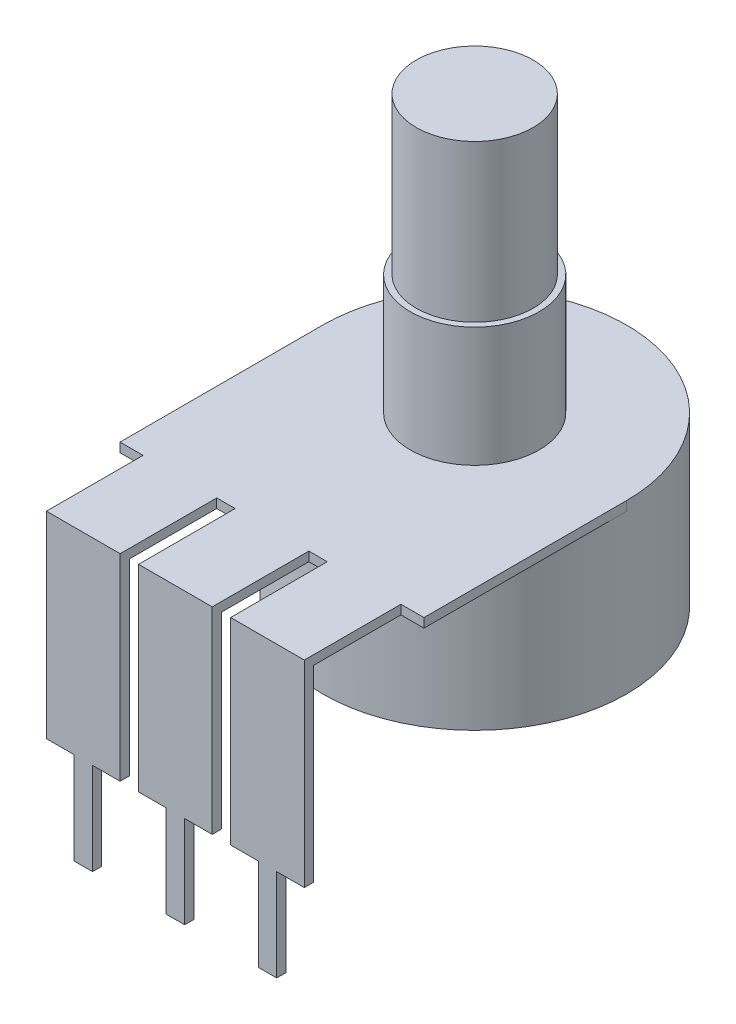
SolidWorks part; units mm, degrees
ref_plane "Front Plane" through (0, 0, 0) normal (0, 0, 1) x (1, 0, 0)
ref_plane "Top Plane" through (0, 0, 0) normal (0, 1, 0) x (1, 0, 0)
ref_plane "Right Plane" through (0, 0, 0) normal (1, 0, 0) x (0, 0, -1)
sketch "Sketch1" plane through (0, 0, 0) normal (0, 1, 0) x (1, 0, 0)
  circle A0 centre (0, 0) radius 8.25
  dimension "D1" = 16.5
extrude "Boss-Extrude1" add sketch "Sketch1" along normal blind 9.1
sketch "Sketch2" plane through (0, 9.1, 0) normal (0, 1, 0) x (1, 0, 0)
  circle A0 centre (0, 0) radius 3.5
  dimension "D1" = 7
extrude "Boss-Extrude2" add sketch "Sketch2" along normal blind 6.5
sketch "Sketch3" plane through (0, 15.6, 0) normal (0, 1, 0) x (1, 0, 0)
  circle A0 centre (0, 0) radius 3.175
  dimension "D1" = 6.35
extrude "Boss-Extrude3" add sketch "Sketch3" along normal blind 8.5
sketch "Sketch4" plane through (0, 9.1, 0) normal (0, 1, 0) x (1, 0, 0)
  line L0 (-8.25, 0) -> (-8.25, -16.25)
  line L1 (8.25, 0) -> (8.25, -16.25)
  line L2 (-8.25, -16.25) -> (8.25, -16.25)
  circle A0 centre (0, 0) radius 8.25 construction
  arc A1 (-8.25, 0) -> (8.25, 0) centre (0, 0) ccw
  dimension "D1" = 16.25
extrude "Boss-Extrude4" add sketch "Sketch4" against normal blind 0.5
sketch "Sketch5" plane through (0, 8.6, 0) normal (0, -1, 0) x (1, 0, 0)
  line L0 (0, 16.25) -> (0, 16) construction
  line L1 (-8.25, 16.25) -> (8.25, 16.25) construction
  line L2 (0, 16) -> (-5, 16) construction
  line L3 (-2, 16.25) -> (2, 16.25)
  line L4 (-2, 16.25) -> (-2, 15.75)
  line L5 (-2, 15.75) -> (2, 15.75)
  line L6 (2, 16.25) -> (2, 15.75)
  line L7 (-2, 16.25) -> (2, 15.75) construction
  line L8 (-2, 15.75) -> (2, 16.25) construction
  line L9 (0, 16) -> (5, 16) construction
  line L11 (-7, 16.25) -> (-3, 16.25)
  line L12 (-7, 16.25) -> (-7, 15.75)
  line L13 (-7, 15.75) -> (-3, 15.75)
  line L14 (-3, 16.25) -> (-3, 15.75)
  line L15 (-7, 16.25) -> (-3, 15.75) construction
  line L16 (-7, 15.75) -> (-3, 16.25) construction
  line L17 (3, 16.25) -> (7, 16.25)
  line L18 (3, 16.25) -> (3, 15.75)
  line L19 (3, 15.75) -> (7, 15.75)
  line L20 (7, 16.25) -> (7, 15.75)
  line L21 (3, 16.25) -> (7, 15.75) construction
  line L22 (3, 15.75) -> (7, 16.25) construction
  dimension "D1" = 5
  dimension "D2" = 5
  dimension "D3" = 0.5
  dimension "D4" = 4
extrude "Boss-Extrude5" add sketch "Sketch5" along normal offset from surface (10.2 mm away) 10.7 up to face at (0, 9.1, 3.5)
sketch "Sketch6" plane through (0, -1.6, 0) normal (0, -1, 0) x (1, 0, 0)
  line L0 (-5, 16.25) -> (-5, 15.75) construction
  line L1 (-7, 16.25) -> (-3, 16.25) construction
  line L2 (-7, 15.75) -> (-3, 15.75) construction
  line L3 (0, 16.25) -> (0, 15.75) construction
  line L4 (-2, 16.25) -> (2, 16.25) construction
  line L5 (-2, 15.75) -> (2, 15.75) construction
  line L6 (5, 16.25) -> (5, 15.75) construction
  line L7 (3, 16.25) -> (7, 16.25) construction
  line L8 (7, 15.75) -> (3, 15.75) construction
  line L9 (3, 15.75) -> (7, 15.75) construction
  line L10 (4.5, 16.25) -> (5.5, 16.25)
  line L11 (4.5, 16.25) -> (4.5, 15.75)
  line L12 (4.5, 15.75) -> (5.5, 15.75)
  line L13 (5.5, 16.25) -> (5.5, 15.75)
  line L14 (4.5, 16.25) -> (5.5, 15.75) construction
  line L15 (4.5, 15.75) -> (5.5, 16.25) construction
  line L17 (-0.5, 16.25) -> (0.5, 16.25)
  line L18 (-0.5, 16.25) -> (-0.5, 15.75)
  line L19 (-0.5, 15.75) -> (0.5, 15.75)
  line L20 (0.5, 16.25) -> (0.5, 15.75)
  line L21 (-0.5, 16.25) -> (0.5, 15.75) construction
  line L22 (-0.5, 15.75) -> (0.5, 16.25) construction
  line L23 (-5.5, 16.25) -> (-4.5, 16.25)
  line L24 (-5.5, 16.25) -> (-5.5, 15.75)
  line L25 (-5.5, 15.75) -> (-4.5, 15.75)
  line L26 (-4.5, 16.25) -> (-4.5, 15.75)
  line L27 (-5.5, 16.25) -> (-4.5, 15.75) construction
  line L28 (-5.5, 15.75) -> (-4.5, 16.25) construction
  point P18 (5, 16)
  point P25 (0, 16)
  point P30 (-5, 16)
  dimension "D1" = 1
extrude "Boss-Extrude6" add sketch "Sketch6" along normal blind 5
sketch "Sketch7" plane through (0, 9.1, 0) normal (0, 1, 0) x (1, 0, 0)
  line L0 (-8.25, -16.25) -> (8.25, -16.25) construction
  line L1 (-8.25, -16.25) -> (-7, -16.25)
  line L2 (-8.25, -16.25) -> (-8.25, -11.0056)
  line L3 (-8.25, -11.0056) -> (-7, -11.0056)
  line L4 (-7, -16.25) -> (-7, -11.0056)
  line L5 (8.25, -16.25) -> (7, -16.25)
  line L6 (8.25, -16.25) -> (8.25, -11.0056)
  line L7 (8.25, -11.0056) -> (7, -11.0056)
  line L8 (7, -16.25) -> (7, -11.0056)
  line L9 (3, -16.25) -> (2, -16.25)
  line L10 (3, -16.25) -> (3, -11.0056)
  line L11 (3, -11.0056) -> (2, -11.0056)
  line L12 (2, -16.25) -> (2, -11.0056)
  line L14 (-3, -16.25) -> (-2, -16.25)
  line L15 (-3, -16.25) -> (-3, -11.0056)
  line L16 (-3, -11.0056) -> (-2, -11.0056)
  line L17 (-2, -16.25) -> (-2, -11.0056)
extrude "Cut-Extrude1" cut sketch "Sketch7" against normal up to next
